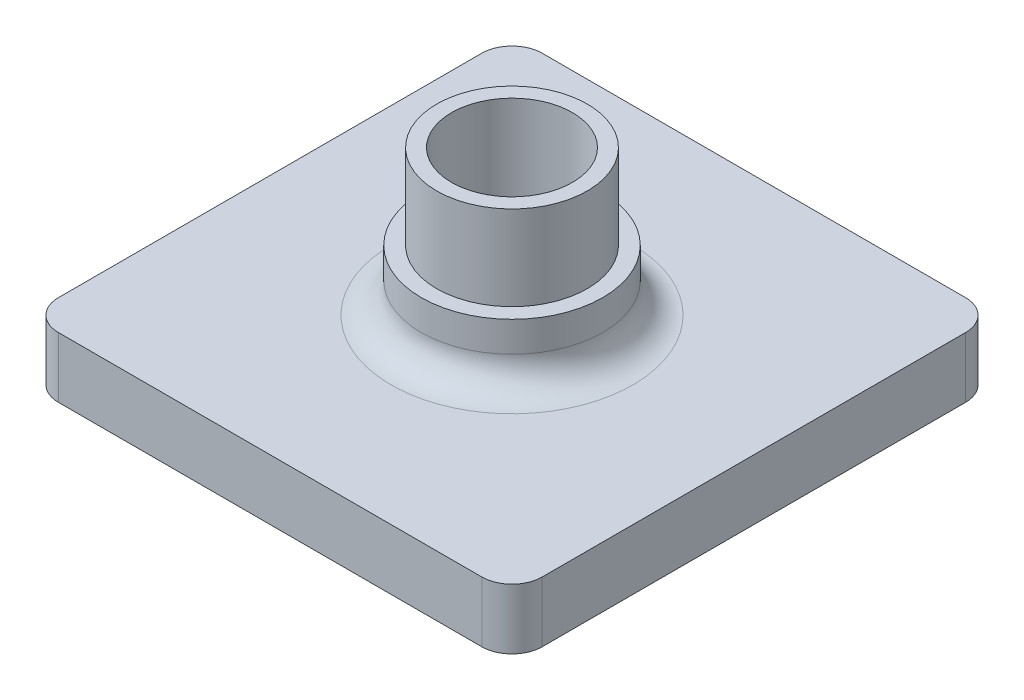
SolidWorks part; units mm, degrees
ref_plane "Front Plane" through (0, 0, 0) normal (0, 0, 1) x (1, 0, 0)
ref_plane "Top Plane" through (0, 0, 0) normal (0, 1, 0) x (1, 0, 0)
ref_plane "Right Plane" through (0, 0, 0) normal (1, 0, 0) x (0, 0, -1)
sketch "Sketch1" plane through (0, 0, 0) normal (0, 1, 0) x (1, 0, 0)
  line L1 (-20, -20) -> (20, -20)
  line L2 (-20, -20) -> (-20, 20)
  line L3 (-20, 20) -> (20, 20)
  line L4 (20, -20) -> (20, 20)
  line L5 (-20, -20) -> (20, 20) construction
  line L6 (-20, 20) -> (20, -20) construction
  point P0 (0, 0)
  dimension "D1" = 40
  dimension "D2" = 40
extrude "Boss-Extrude1" add sketch "Sketch1" along normal blind 5
sketch "Sketch2" plane through (0, 5, 0) normal (0, 1, 0) x (1, 0, 0)
  circle A0 centre (0, 0) radius 7.5
  dimension "D1" = 15
extrude "Boss-Extrude2" add sketch "Sketch2" along normal blind 5
sketch "Sketch4" plane through (0, 10, 0) normal (0, 1, 0) x (1, 0, 0)
  circle A0 centre (0, 0) radius 6.225
  dimension "D1" = 12.45
extrude "Boss-Extrude3" add sketch "Sketch4" along normal blind 7
fillet "Fillet1" radius 2.5 5 edges at (0, 5, 7.5) (-20, 2.5, 20) (-20, 2.5, -20) (20, 2.5, -20) (20, 2.5, 20)
sketch "Sketch5" plane through (0, 17, 0) normal (0, 1, 0) x (1, 0, 0)
  circle A0 centre (0, 0) radius 5
  dimension "D1" = 10
extrude "Cut-Extrude1" cut sketch "Sketch5" against normal blind 17
